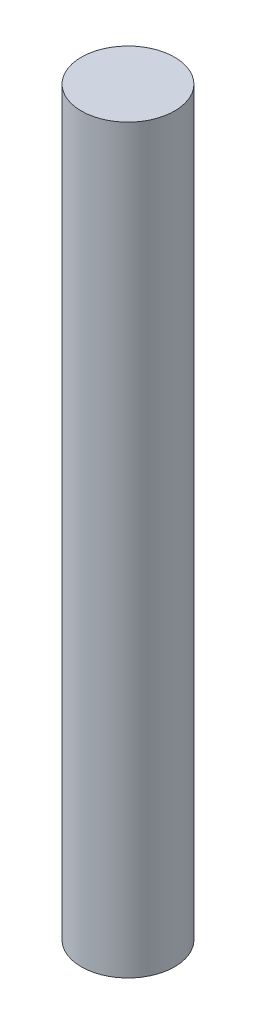
SolidWorks part; units mm, degrees
ref_plane "Front Plane" through (0, 0, 0) normal (0, 0, 1) x (1, 0, 0)
ref_plane "Top Plane" through (0, 0, 0) normal (0, 1, 0) x (1, 0, 0)
ref_plane "Right Plane" through (0, 0, 0) normal (1, 0, 0) x (0, 0, -1)
sketch "Sketch1" plane through (0, 0, 0) normal (0, 1, 0) x (1, 0, 0)
  circle A0 centre (0, 0) radius 2.1082
  dimension "D1" = 4.2164
extrude "Boss-Extrude1" add sketch "Sketch1" along normal blind 33.5
